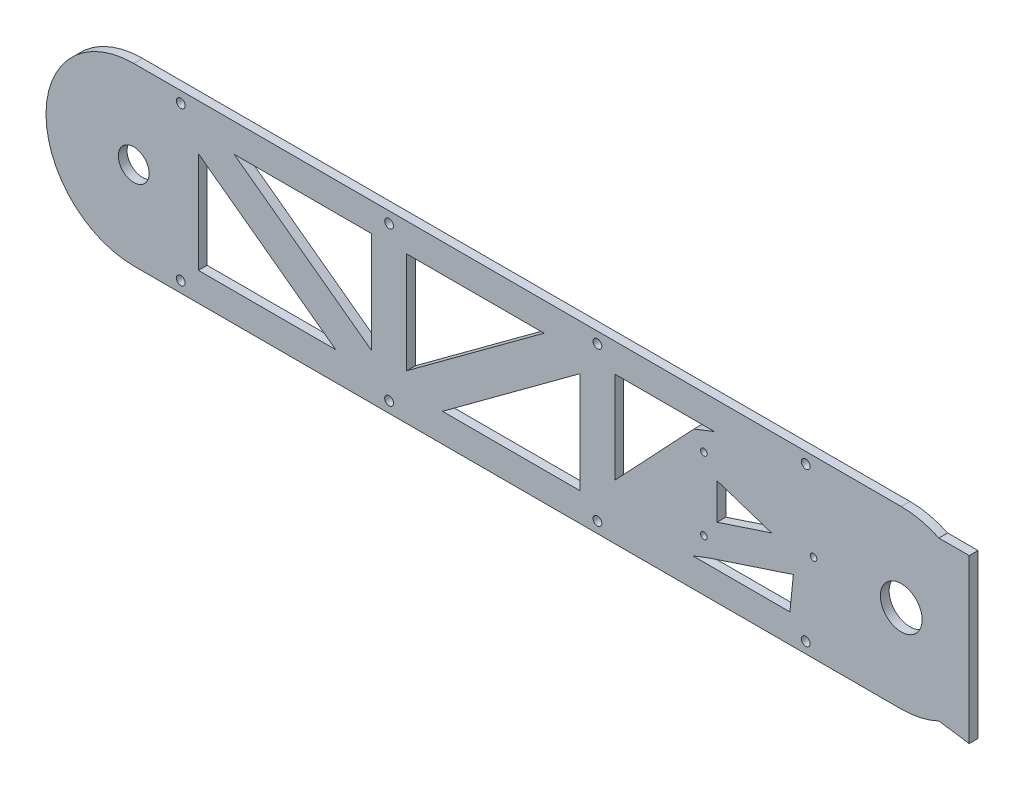
SolidWorks part; units mm, degrees
ref_plane "前视基准面" through (0, 0, 0) normal (0, 0, 1) x (1, 0, 0)
ref_plane "上视基准面" through (0, 0, 0) normal (0, 1, 0) x (1, 0, 0)
ref_plane "右视基准面" through (0, 0, 0) normal (1, 0, 0) x (0, 0, -1)
sketch "草图1" plane through (0, 0, 0) normal (0, 0, 1) x (1, 0, 0)
  line L0 (348.5429, -0.1457) -> (-1.4571, -0.1457) construction
  line L1 (348.5429, 39.8543) -> (-1.4571, 39.8543)
  line L7 (348.5429, -40.1457) -> (-1.4571, -40.1457)
  circle A0 centre (-1.4571, -0.1457) radius 7.03
  circle A1 centre (-1.4571, -0.1457) radius 40 construction
  arc A4 (-1.4571, 39.8543) -> (-1.4571, -40.1457) centre (-1.4571, -0.1457) ccw
  circle A11 centre (348.5429, -0.1457) radius 9.53
  circle A12 centre (348.5429, -0.1457) radius 40 construction
  arc A13 (348.5429, 39.8543) -> (348.5429, -40.1457) centre (348.5429, -0.1457) cw
  circle A16 centre (348.5429, -0.1457) radius 30 construction
  circle A17 centre (308.5429, -0.1457) radius 1.5
  circle A18 centre (258.5429, 16.3543) radius 1.5
  circle A19 centre (258.5429, -16.6457) radius 1.5
  dimension "D1" = 350
  dimension "D2" = 14.06
  dimension "D3" = 50
  dimension "D4" = 19.06
  dimension "D5" = 80
  dimension "D6" = 16.5
extrude "凸台-拉伸1" add sketch "草图1" along normal blind 4 contours A13
sketch "草图2" plane through (0, 0, 4) normal (0, 0, 1) x (1, 0, 0)
  line L0 (348.5429, 39.8543) -> (-1.4571, 39.8543) construction
  line L1 (-1.4571, -0.1457) -> (348.5429, -0.1457) construction
  line L2 (20, 34.8543) -> (115, 34.8543) construction
  line L3 (115, 34.8543) -> (115, -35.1457) construction
  line L4 (115, -35.1457) -> (20, 34.8543) construction
  line L5 (20, -35.1457) -> (115, -35.1457) construction
  line L6 (20, 34.8543) -> (20, -35.1457) construction
  line L7 (44.3433, 26.8543) -> (107, 26.8543)
  line L8 (107, 26.8543) -> (107, -19.3138)
  line L9 (107, -19.3138) -> (44.3433, 26.8543)
  line L10 (28, 19.0223) -> (28, -27.1457)
  line L11 (28, -27.1457) -> (90.6567, -27.1457)
  line L12 (90.6567, -27.1457) -> (28, 19.0223)
  line L13 (115, -35.1457) -> (210, 34.8543)
  line L14 (210, 34.8543) -> (210, -35.1457) construction
  line L15 (210, -35.1457) -> (115, -35.1457) construction
  line L16 (115, 34.8543) -> (210, 34.8543) construction
  line L17 (139.3433, -27.1457) -> (202, 19.0223)
  line L18 (202, 19.0223) -> (202, -27.1457)
  line L19 (202, -27.1457) -> (139.3433, -27.1457)
  line L20 (123, 26.8543) -> (185.6567, 26.8543)
  line L21 (123, -19.3138) -> (185.6567, 26.8543)
  line L22 (123, 26.8543) -> (123, -19.3138)
  line L23 (210, 34.8543) -> (305, 34.8543) construction
  line L24 (305, 34.8543) -> (258.5429, 16.3543) construction
  line L25 (258.5429, 16.3543) -> (210, -35.1457) construction
  line L26 (218, 26.8543) -> (263.2866, 26.8543)
  line L27 (263.2866, 26.8543) -> (253.9368, 23.1311)
  line L28 (253.9368, 23.1311) -> (218, -14.995)
  line L29 (218, 26.8543) -> (218, -14.995)
  line L30 (210, -35.1457) -> (305, -35.1457) construction
  line L31 (305, -35.1457) -> (308.5429, -0.1457) construction
  line L32 (308.5429, -0.1457) -> (258.5429, -16.6457) construction
  line L33 (258.5429, -16.6457) -> (210, -35.1457) construction
  line L34 (299.3419, -11.6064) -> (261.2222, -24.1859)
  line L35 (261.2222, -24.1859) -> (253.4558, -27.1457)
  line L36 (253.4558, -27.1457) -> (297.7689, -27.1457)
  line L37 (297.7689, -27.1457) -> (299.3419, -11.6064)
  line L38 (258.5429, 16.3543) -> (258.5429, -16.6457) construction
  line L39 (308.5429, -0.1457) -> (258.5429, 16.3543) construction
  line L40 (289.3966, -0.1457) -> (264.5429, 8.056)
  line L41 (264.5429, 8.056) -> (264.5429, -8.3475)
  line L42 (289.3966, -0.1457) -> (264.5429, -8.3475)
  circle A0 centre (20, 34.8543) radius 2
  circle A1 centre (115, 34.8543) radius 2
  circle A2 centre (210, 34.8543) radius 2
  circle A3 centre (305, 34.8543) radius 2
  circle A4 centre (305, -35.1457) radius 2
  circle A5 centre (210, -35.1457) radius 2
  circle A6 centre (115, -35.1457) radius 2
  circle A7 centre (20, -35.1457) radius 2
  dimension "D1" = 5
  dimension "D2" = 20
  dimension "D4" = 8
  dimension "D5" = 8
  dimension "D6" = 8
  dimension "D7" = 8
  dimension "D8" = 8
  dimension "D9" = 8
  dimension "D10" = 6
  dimension "D3" = 4
extrude "切除-拉伸1" cut sketch "草图2" against normal blind 10
sketch "草图3" plane through (0, 0, 0) normal (0, 0, -1) x (-1, 0, 0)
  line L0 (-348.5429, -0.1457) -> (-379.5429, -0.1457) construction
  line L1 (-379.5429, -0.1457) -> (-379.5429, 86.7114)
  line L2 (-379.5429, 86.7114) -> (-469.1394, 65.162)
  line L3 (-469.1394, 65.162) -> (-431.7972, -71.6228)
  line L4 (-431.7972, -71.6228) -> (-379.5429, -46.8989)
  line L5 (-379.5429, -46.8989) -> (-379.5429, -0.1457)
extrude "切除-拉伸4" cut sketch "草图3" against normal blind 4
sketch "草图4" plane through (0, 0, 0) normal (0, 0, -1) x (-1, 0, 0)
  line L0 (-379.5429, -25.4242) -> (-379.5429, -38.2789)
  line L1 (-379.5429, -38.2789) -> (-365.7018, -36.2784)
  line L2 (-365.7018, -36.2784) -> (-365.7018, 35.9869)
  line L3 (-365.7018, 35.9869) -> (-379.5429, 35.9869)
  line L4 (-379.5429, 35.9869) -> (-379.5429, 25.1327)
  line L5 (-379.5429, -25.4242) -> (-379.5429, 25.1327)
  arc A0 (-379.5429, -25.4242) -> (-348.5429, -40.1457) centre (-348.5429, -0.1457) ccw construction
  arc A1 (-348.5429, 39.8543) -> (-379.5429, 25.1327) centre (-348.5429, -0.1457) ccw construction
extrude "凸台-拉伸2" add sketch "草图4" against normal blind 4
